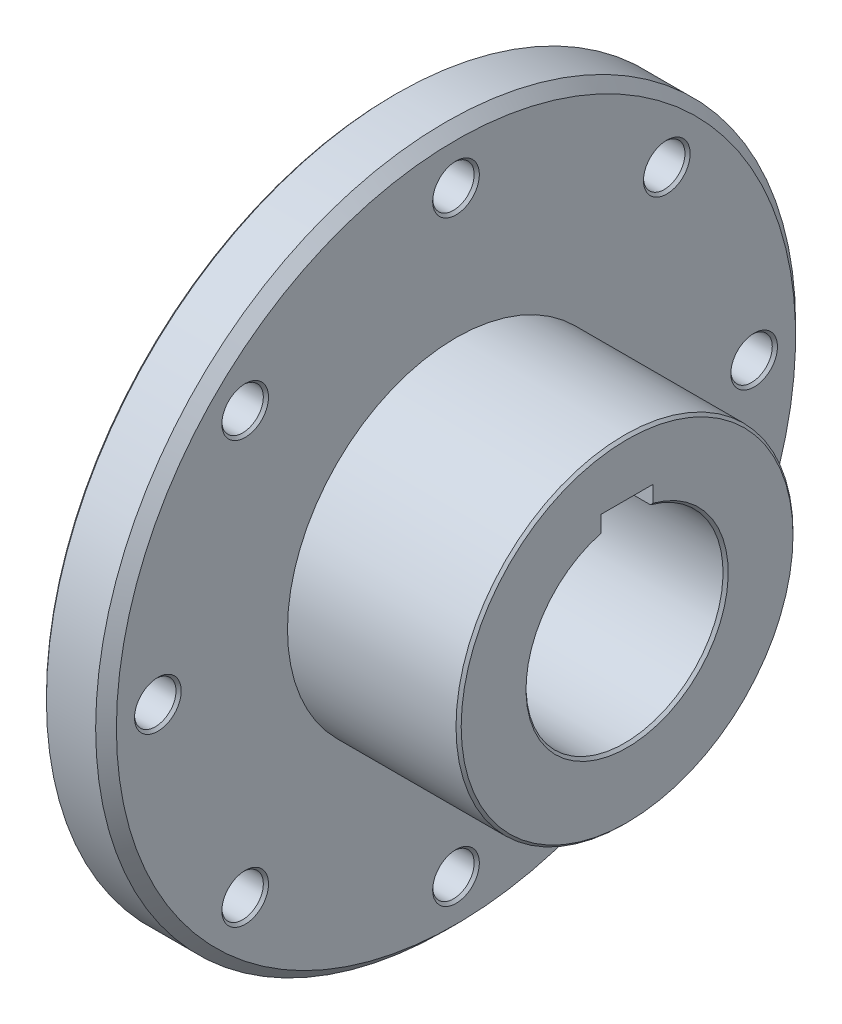
SolidWorks part; units mm, degrees
ref_plane "前视基准面" through (0, 0, 0) normal (0, 0, 1) x (1, 0, 0)
ref_plane "上视基准面" through (0, 0, 0) normal (0, 1, 0) x (1, 0, 0)
ref_plane "右视基准面" through (0, 0, 0) normal (1, 0, 0) x (0, 0, -1)
other "Configuration Table"
sketch "草图1" plane through (0, 0, 0) normal (0, 0, 1) x (1, 0, 0)
  line L0 (0, 0) -> (144.6131, 0) construction
  line L1 (0, 19) -> (0, 32.5)
  line L2 (0, 32.5) -> (10, 32.5)
  line L3 (10, 32.5) -> (10, 67.5)
  line L4 (10, 67.5) -> (22, 67.5)
  line L5 (22, 67.5) -> (22, 32.5)
  line L6 (22, 32.5) -> (55, 32.5)
  line L7 (55, 32.5) -> (55, 19)
  line L8 (55, 19) -> (0, 19)
  dimension "D1" = 135
  dimension "D2" = 55
  dimension "D3" = 10
  dimension "D4" = 22
  dimension "D5" = 65
  dimension "D6" = 38
revolve "旋转1" add sketch "草图1" angle 360 about L0
sketch "草图2" plane through (55, 0, 0) normal (1, 0, 0) x (0, 0, -1)
  line L1 (-5, 22) -> (5, 22)
  line L2 (-5, 22) -> (-5, 0)
  line L3 (-5, 0) -> (5, 0)
  line L4 (5, 22) -> (5, 0)
  line L5 (-5, 22) -> (5, 0) construction
  line L6 (-5, 0) -> (5, 22) construction
  circle A4 centre (0, 0) radius 19 construction
  point P0 (0, 11)
  point P8 (0, 0)
  dimension "D1" = 41
  dimension "D2" = 10
extrude "切除-拉伸1" cut sketch "草图2" against normal through all
sketch "草图3" plane through (22, 0, 0) normal (1, 0, 0) x (0, 0, -1)
  circle A0 centre (0, 0) radius 57.5 construction
  circle A1 centre (0, 57.5) radius 4
  circle A2 centre (40.6586, 40.6586) radius 4
  circle A3 centre (57.5, 0) radius 4
  circle A4 centre (40.6586, -40.6586) radius 4
  circle A5 centre (0, -57.5) radius 4
  circle A6 centre (-40.6586, -40.6586) radius 4
  circle A7 centre (-57.5, 0) radius 4
  circle A8 centre (-40.6586, 40.6586) radius 4
  point P5 (-36.4211, 36.8825)
  point P6 (0, 0)
  point P21 (0, 0)
  dimension "D1" = 115
  dimension "D2" = 8
  dimension "D3" = 8
extrude "切除-拉伸2" cut sketch "草图3" against normal through all
chamfer "倒角1" distance 2 angle 45 1 edges at (22, 0, 67.5)
chamfer "倒角2" distance 1 angle 45 1 edges at (0, -19, 0)
chamfer "倒角3" distance 0.5 angle 45 19 edges at (55, 0, 32.5) (10, 0, 67.5) (10, 40.6586, 36.6586) (10, 0, 53.5) (10, -40.6586, 36.6586) (10, -57.5, -4) (10, -40.6586, -44.6586) (10, 0, -61.5) (10, 40.6586, -44.6586) (10, 57.5, -4) (22, 40.6586, 36.6586) (22, 57.5, -4) (22, 0, -61.5) (22, 40.6586, -44.6586) (22, -40.6586, -44.6586) (22, -57.5, -4) (22, -40.6586, 36.6586) (22, 0, 53.5) (55, -19, 0)
